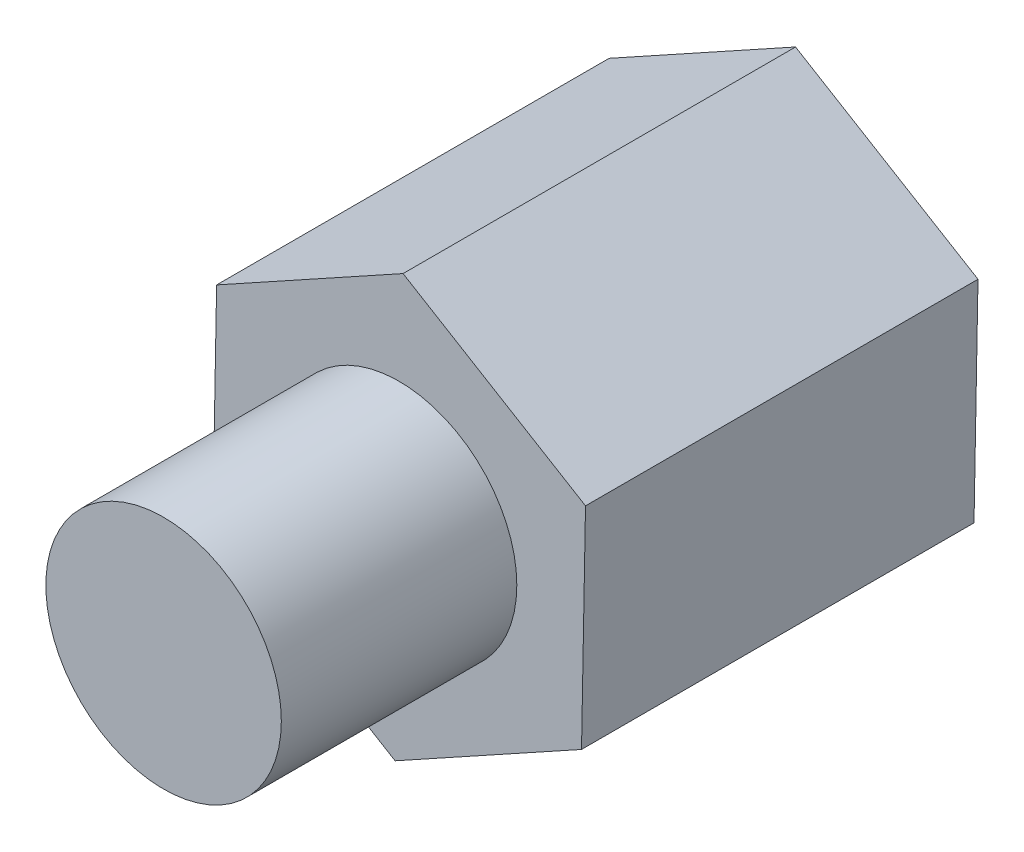
SolidWorks part; units mm, degrees
ref_plane "前视基准面" through (0, 0, 0) normal (0, 0, 1) x (1, 0, 0)
ref_plane "上视基准面" through (0, 0, 0) normal (0, 1, 0) x (1, 0, 0)
ref_plane "右视基准面" through (0, 0, 0) normal (1, 0, 0) x (0, 0, -1)
other "Configuration Table"
sketch "草图1" plane through (0, 0, 0) normal (0, 0, 1) x (1, 0, 0)
  line L1 (-2.3242, 1.4005) -> (-2.375, -1.3126)
  line L2 (-2.375, -1.3126) -> (-0.0508, -2.7131)
  line L3 (-0.0508, -2.7131) -> (2.3242, -1.4005)
  line L4 (2.3242, -1.4005) -> (2.375, 1.3126)
  line L5 (2.375, 1.3126) -> (0.0508, 2.7131)
  line L6 (0.0508, 2.7131) -> (-2.3242, 1.4005)
  circle A0 centre (0, 0) radius 2.35 construction
  point P1 (-1.1367, 2.0568)
  point P10 (1.1367, -2.0568)
  dimension "D1" = 4.7
extrude "凸台-拉伸1" add sketch "草图1" along normal blind 5
sketch "草图2" plane through (0, 0, 5) normal (0, 0, 1) x (1, 0, 0)
  circle A0 centre (0, 0) radius 1.5
  dimension "D1" = 3
extrude "凸台-拉伸2" add sketch "草图2" along normal blind 3
sketch "草图3" plane through (0, 0, 0) normal (0, 0, -1) x (-1, 0, 0)
  circle A0 centre (0, 0) radius 1.5
  dimension "D1" = 3
extrude "切除-拉伸1" cut sketch "草图3" against normal blind 3
